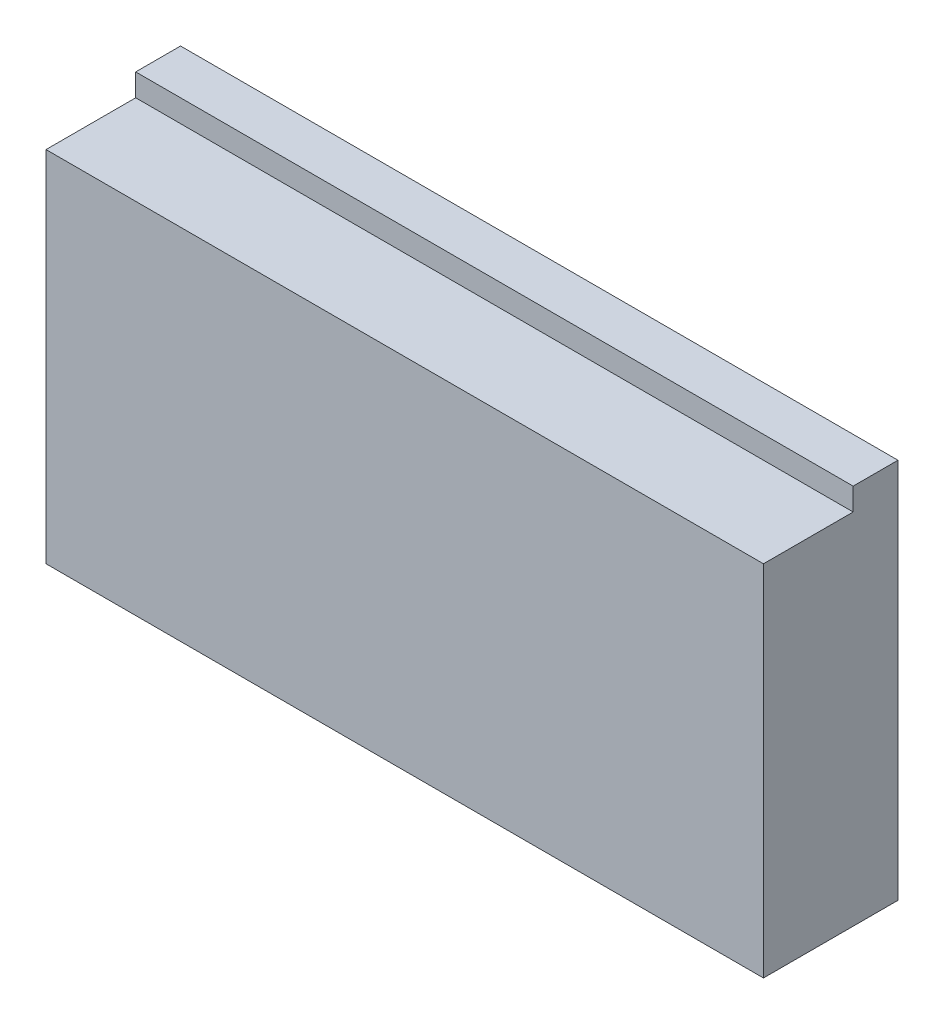
SolidWorks part; units mm, degrees
ref_plane "Plan de face" through (0, 0, 0) normal (0, 0, 1) x (1, 0, 0)
ref_plane "Plan de dessus" through (0, 0, 0) normal (0, 1, 0) x (1, 0, 0)
ref_plane "Plan de droite" through (0, 0, 0) normal (1, 0, 0) x (0, 0, -1)
sketch "Base" plane through (0, 0, 0) normal (0, 1, 0) x (1, 0, 0)
  line L1 (0, 0) -> (32, 0)
  line L2 (0, 0) -> (0, 6)
  line L3 (0, 6) -> (32, 6)
  line L4 (32, 0) -> (32, 6)
  dimension "D1" = 32
  dimension "D2" = 6
extrude "Boss.-Extru.1" add sketch "Base" along normal blind 16
sketch "Esquisse2" plane through (0, 16, 0) normal (0, 1, 0) x (1, 0, 0)
  line L0 (32, 0) -> (32, 6) construction
  line L1 (0, 6) -> (32, 6)
  line L2 (0, 6) -> (0, 4)
  line L3 (0, 4) -> (32, 4)
  line L4 (32, 6) -> (32, 4)
  dimension "D1" = 2
extrude "Boss.-Extru.2" add sketch "Esquisse2" along normal blind 1
sketch "Trou A1" plane through (32, 0, 0) normal (1, 0, 0) x (0, 0, -1)
  line L0 (0, 0) -> (6, 0) construction
  line L1 (6, 17) -> (6, 0) construction
  circle A0 centre (3, 8) radius 0.5
  dimension "D3" = 1
  dimension "D1" = 8
  dimension "D2" = 3
sketch "Trou A2" plane through (0, 0, 0) normal (-1, 0, 0) x (0, 0, 1)
  line L0 (-6, 17) -> (-6, 0) construction
  line L1 (-6, 0) -> (0, 0) construction
  circle A0 centre (-3, 8) radius 0.5
  dimension "D1" = 1
  dimension "D2" = 3
  dimension "D3" = 8
sketch "Trous B" plane through (0, 0, 0) normal (0, -1, 0) x (1, 0, 0)
  line L0 (32, -6) -> (0, -6) construction
  line L1 (0, -6) -> (0, 0) construction
  circle A0 centre (6, -2) radius 0.5
  circle A1 centre (20, -2) radius 0.5
  point P8 (0, 0)
  dimension "D1" = 1
  dimension "D2" = 1
  dimension "D3" = 4
  dimension "D4" = 4
  dimension "D5" = 20
  dimension "D6" = 6
